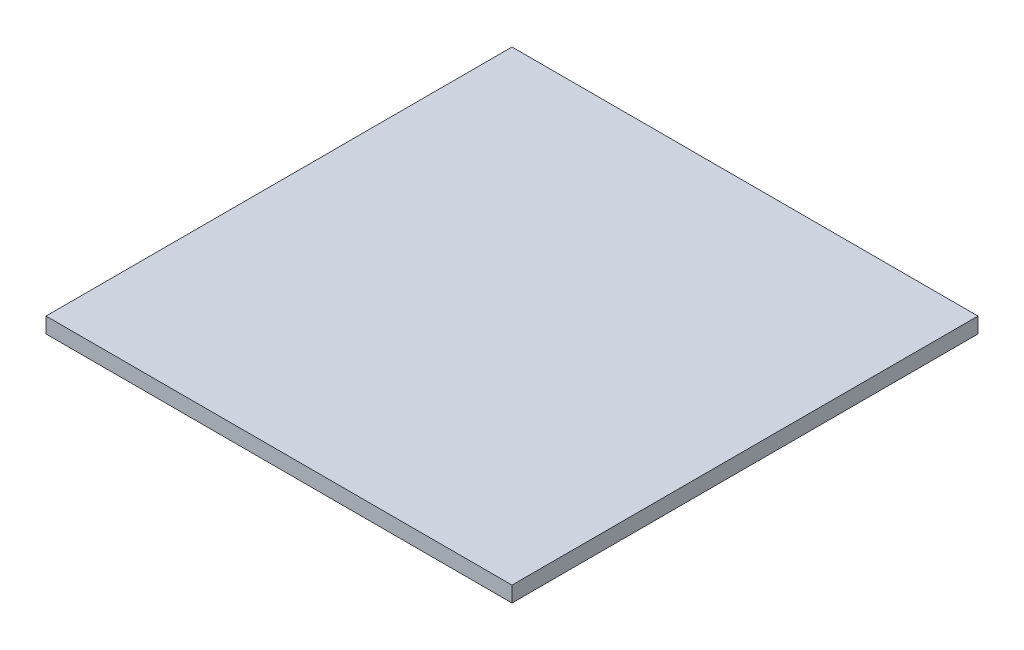
SolidWorks part; units mm, degrees
ref_plane "Front Plane" through (0, 0, 0) normal (0, 0, 1) x (1, 0, 0)
ref_plane "Top Plane" through (0, 0, 0) normal (0, 1, 0) x (1, 0, 0)
ref_plane "Right Plane" through (0, 0, 0) normal (1, 0, 0) x (0, 0, -1)
sketch "Sketch1" plane through (0, 0, 0) normal (0, 1, 0) x (1, 0, 0)
  line L1 (-75, 65) -> (75, 65)
  line L2 (-75, 65) -> (-75, -65)
  line L3 (-75, -65) -> (75, -65)
  line L4 (75, 65) -> (75, -65)
  line L5 (-75, 65) -> (75, -65) construction
  line L6 (-75, -65) -> (75, 65) construction
  point P0 (0, 0)
  dimension "D1" = 150
  dimension "D2" = 130
extrude "Boss-Extrude1" add sketch "Sketch1" along normal blind 5
sketch "Sketch2" plane through (0, 0, 65) normal (0, 0, 1) x (1, 0, 0)
  line L1 (-75, 5) -> (75, 5)
  line L2 (-75, 5) -> (-75, 0)
  line L3 (-75, 0) -> (75, 0)
  line L4 (75, 5) -> (75, 0)
extrude "Boss-Extrude2" add sketch "Sketch2" along normal blind 20
